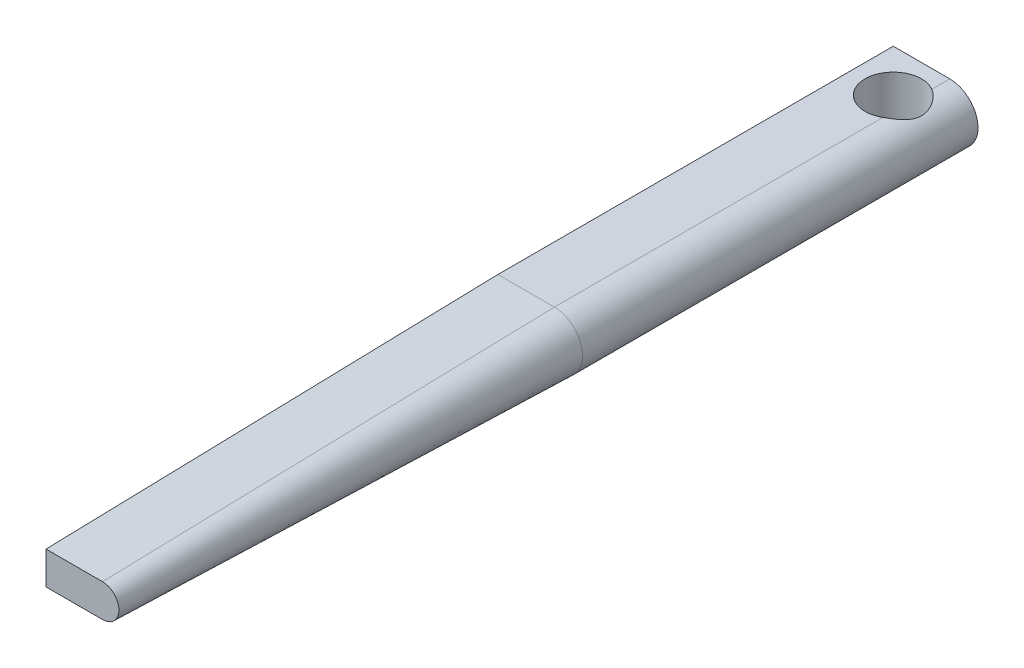
SolidWorks part; units mm, degrees
ref_plane "前视基准面" through (0, 0, 0) normal (0, 0, 1) x (1, 0, 0)
ref_plane "上视基准面" through (0, 0, 0) normal (0, 1, 0) x (1, 0, 0)
ref_plane "右视基准面" through (0, 0, 0) normal (1, 0, 0) x (0, 0, -1)
sketch "草图1" plane through (0, 0, 0) normal (0, 0, 1) x (1, 0, 0)
  line L1 (0, 10) -> (10, 10)
  line L2 (0, 10) -> (0, 0)
  line L3 (0, 0) -> (10, 0)
  arc A0 (10, 10) -> (10, 0) centre (10, 5) cw
  dimension "D1" = 10
extrude "拉伸1" add sketch "草图1" along normal blind 150
sketch "草图2" plane through (0, 10, 0) normal (0, 1, 0) x (1, 0, 0)
  line L0 (0, -150) -> (0, 0) construction
  line L2 (10, 0) -> (0, 0) construction
  circle A0 centre (7.5, -7.5) radius 5
  dimension "D1" = 10
  dimension "D2" = 7.5
  dimension "D3" = 7.5
extrude "拉伸2" cut sketch "草图2" against normal through all
chamfer "倒角1" distance 80 angle 1.5 3 edges at (5, 0, 150) (15, 5, 150) (5, 10, 150)
